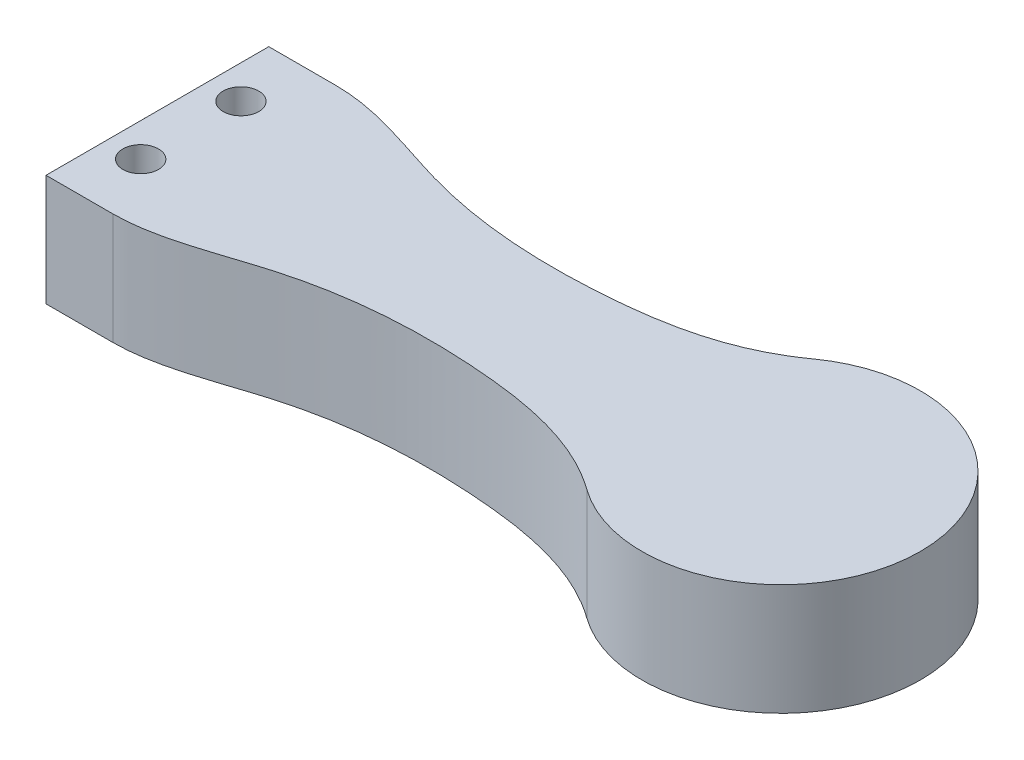
SolidWorks part; units mm, degrees
ref_plane "Front Plane" through (0, 0, 0) normal (0, 0, 1) x (1, 0, 0)
ref_plane "Top Plane" through (0, 0, 0) normal (0, 1, 0) x (1, 0, 0)
ref_plane "Right Plane" through (0, 0, 0) normal (1, 0, 0) x (0, 0, -1)
sketch "Sketch1" plane through (0, 0, 0) normal (0, 1, 0) x (1, 0, 0)
  line L0 (3, 4.5) -> (53, 4.5) construction
  line L1 (-3, 14.5) -> (3, 14.5)
  line L2 (-3, 14.5) -> (-3, -5.5)
  line L3 (-3, -5.5) -> (3, -5.5)
  circle A0 centre (0, 0) radius 1.6
  circle A1 centre (0, 9) radius 1.6
  arc A2 (45.7096, -5.6538) -> (45.7096, 14.6538) centre (53, 4.5) ccw
  spline S0 degree 3 poles (3, -5.5) (7.1147, -5.5) (16.3202, -1.3168) (31.0774, -0.5956) (41.4425, -2.5901) (45.7096, -5.6538) knots 0 0 0 0 0.285144 0.663252 1 1 1 1
  spline S1 degree 3 poles (3, 14.5) (7.1147, 14.5) (16.3202, 10.3168) (31.0774, 9.5956) (41.4425, 11.5901) (45.7096, 14.6538) knots 0 0 0 0 0.285144 0.663252 1 1 1 1
  point P9 (3, 4.5)
  point P10 (0, -5.5)
  point P19 (3.2149, 4.5)
  point P20 (0, 0)
  dimension "D2" = 3.2
  dimension "D6" = 25
  dimension "D1" = 4.5
  dimension "D3" = 6
  dimension "D4" = 20
  dimension "D5" = 4.5
  dimension "D7" = 50
extrude "Boss-Extrude1" add sketch "Sketch1" along normal blind 10 contours S1 A2 S0 L3 L2 L1 | A1 | A0
